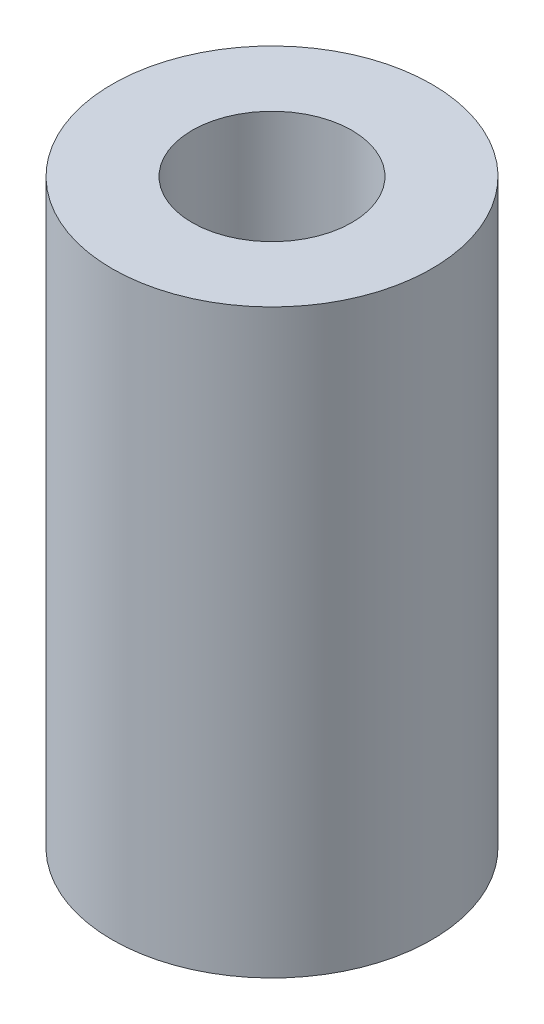
SolidWorks part; units mm, degrees
ref_plane "Front Plane" through (0, 0, 0) normal (0, 0, 1) x (1, 0, 0)
ref_plane "Top Plane" through (0, 0, 0) normal (0, 1, 0) x (1, 0, 0)
ref_plane "Right Plane" through (0, 0, 0) normal (1, 0, 0) x (0, 0, -1)
sketch "Sketch1" plane through (0, 0, 0) normal (0, 1, 0) x (1, 0, 0)
  circle A0 centre (0, 0) radius 1.375
  circle A1 centre (0, 0) radius 2.75
  dimension "D1" = 2.75
  dimension "D2" = 5.5
extrude "Boss-Extrude1" add sketch "Sketch1" along normal blind 10
